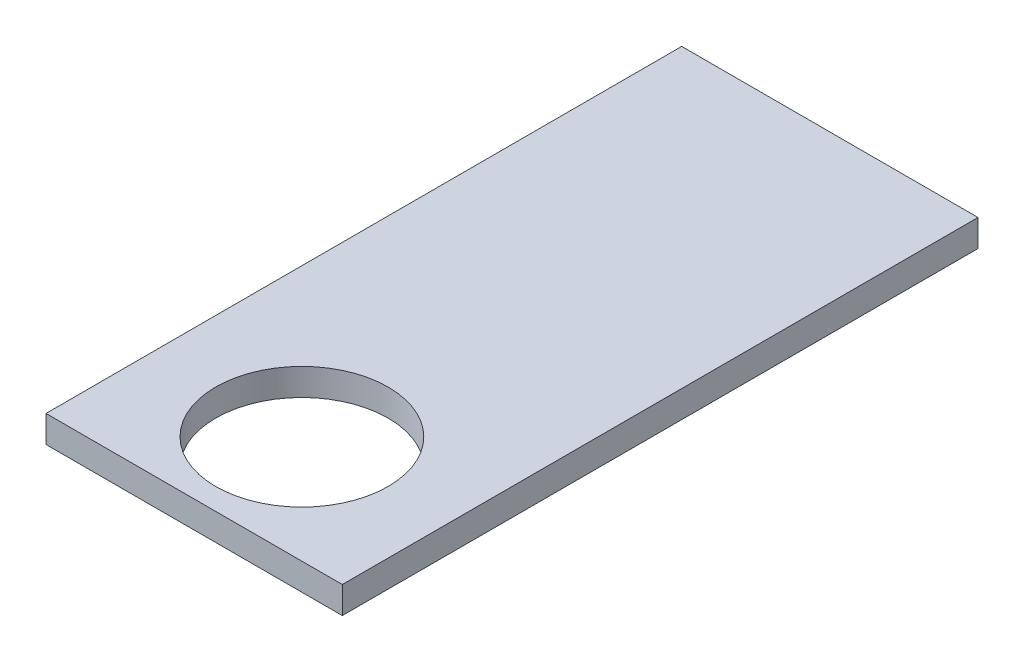
SolidWorks part; units mm, degrees
ref_plane "Front Plane" through (0, 0, 0) normal (0, 0, 1) x (1, 0, 0)
ref_plane "Top Plane" through (0, 0, 0) normal (0, 1, 0) x (1, 0, 0)
ref_plane "Right Plane" through (0, 0, 0) normal (1, 0, 0) x (0, 0, -1)
sketch "Sketch1" plane through (0, 0, 0) normal (0, 1, 0) x (1, 0, 0)
  line L1 (-27.5, 59) -> (27.5, 59)
  line L2 (-27.5, 59) -> (-27.5, -59)
  line L3 (-27.5, -59) -> (27.5, -59)
  line L4 (27.5, 59) -> (27.5, -59)
  line L5 (-27.5, 59) -> (27.5, -59) construction
  line L6 (-27.5, -59) -> (27.5, 59) construction
  circle A0 centre (0, -39) radius 16
  point P0 (0, 0)
  dimension "D3" = 32
  dimension "D1" = 55
  dimension "D2" = 118
  dimension "D4" = 20
extrude "Boss-Extrude1" add sketch "Sketch1" along normal blind 5
